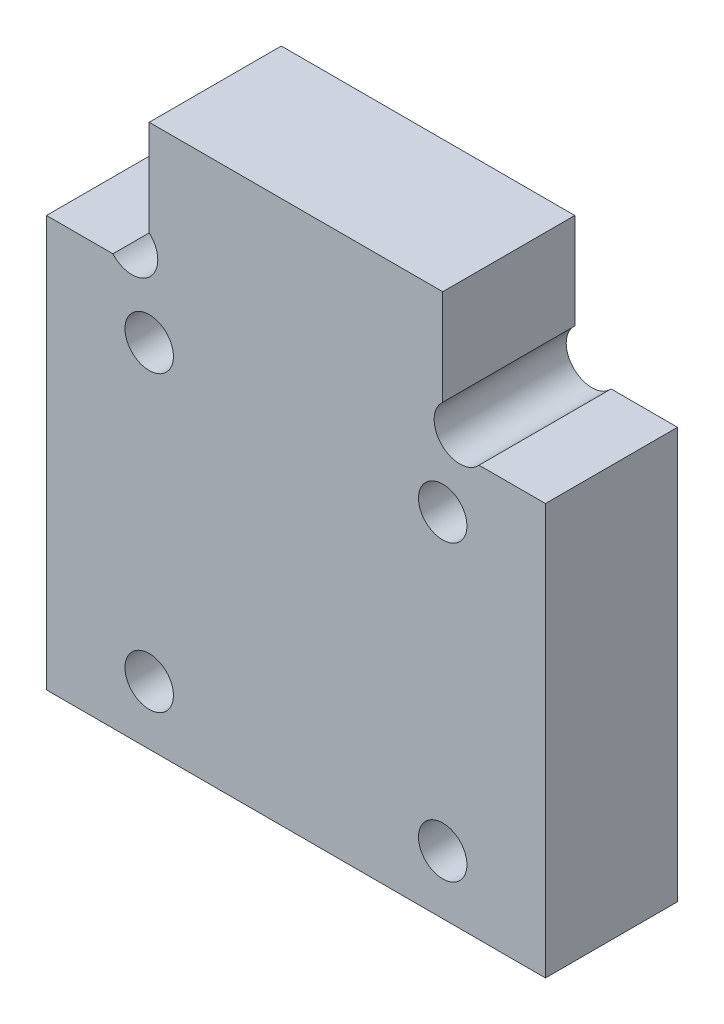
SolidWorks part; units mm, degrees
ref_plane "Plan de face" through (0, 0, 0) normal (0, 0, 1) x (1, 0, 0)
ref_plane "Plan de dessus" through (0, 0, 0) normal (0, 1, 0) x (1, 0, 0)
ref_plane "Plan de droite" through (0, 0, 0) normal (1, 0, 0) x (0, 0, -1)
sketch "Esquisse1" plane through (0, 0, 0) normal (0, 0, 1) x (1, 0, 0)
  line L1 (0, 0) -> (34, 0)
  line L2 (0, 0) -> (0, 28)
  line L3 (0, 28) -> (34, 28)
  line L4 (34, 0) -> (34, 28)
  dimension "D1" = 28
  dimension "D2" = 34
extrude "Boss.-Extru.1" add sketch "Esquisse1" along normal blind 9
sketch "Esquisse2" plane through (0, 0, 9) normal (0, 0, 1) x (1, 0, 0)
  line L0 (17, 28) -> (17, 37) construction
  line L1 (34, 28) -> (0, 28) construction
  line L2 (27, 37) -> (7, 37)
  line L3 (7, 37) -> (7, 28)
  line L4 (7, 28) -> (27, 28)
  line L5 (27, 37) -> (27, 28)
  dimension "D1" = 20
  dimension "D2" = 9
extrude "Boss.-Extru.2" add sketch "Esquisse2" against normal up to vertex (9 mm away)
sketch "Esquisse3" plane through (0, 0, 9) normal (0, 0, 1) x (1, 0, 0)
  line L0 (7, 28) -> (0, 28) construction
  line L1 (7, 37) -> (7, 28) construction
  line L2 (4.5251, 28) -> (7, 30.4749)
  line L3 (5.8314, 29.1686) -> (5.7626, 29.2374) construction
  line L4 (7, 28) -> (7.0707, 27.9293) construction
  line L5 (17, 37) -> (17, 32.4749) construction
  line L6 (27, 37) -> (7, 37) construction
  line L7 (27, 28) -> (26.9293, 27.9293) construction
  line L8 (28.1686, 29.1686) -> (28.2374, 29.2374) construction
  line L9 (29.4749, 28) -> (27, 30.4749)
  arc A0 (4.5251, 28) -> (7, 30.4749) centre (5.8314, 29.1686) ccw
  arc A1 (29.4749, 28) -> (27, 30.4749) centre (28.1686, 29.1686) cw
  dimension "D1" = 3.5
  dimension "D2" = 0.1
extrude "Enlèv. mat.-Extru.1" cut sketch "Esquisse3" against normal through all both and the other way through all
sketch "Esquisse4" plane through (0, 0, 9) normal (0, 0, 1) x (1, 0, 0)
  line L0 (0, 14) -> (34, 14) construction
  line L1 (0, 28) -> (0, 0) construction
  line L2 (34, 0) -> (34, 28) construction
  line L3 (17, 14) -> (17, 21.7109) construction
  line L4 (0, 0) -> (34, 0) construction
  circle A0 centre (7, 24) radius 1.65
  circle A1 centre (27, 24) radius 1.65
  circle A2 centre (27, 4) radius 1.65
  circle A3 centre (7, 4) radius 1.65
  dimension "D1" = 20
  dimension "D2" = 3.3
  dimension "D3" = 20
  dimension "D4" = 14
extrude "Enlèv. mat.-Extru.2" cut sketch "Esquisse4" against normal through all both and the other way through all
